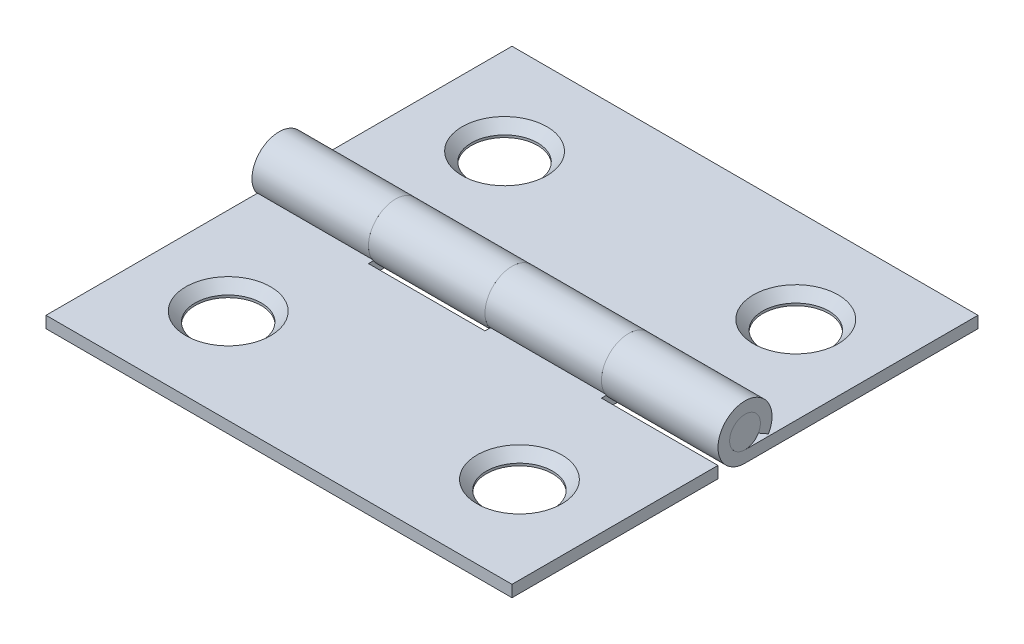
SolidWorks part; units mm, degrees
ref_plane "Front Plane" through (0, 0, 0) normal (0, 0, 1) x (1, 0, 0)
ref_plane "Top Plane" through (0, 0, 0) normal (0, 1, 0) x (1, 0, 0)
ref_plane "Right Plane" through (0, 0, 0) normal (1, 0, 0) x (0, 0, -1)
sketch "Sketch1" plane through (0, 0, 0) normal (0, 1, 0) x (1, 0, 0)
  line L0 (-12.7, 0) -> (12.7, 0) construction
  line L1 (-12.7, -12.7) -> (-12.7, 12.7) construction
  line L2 (-12.7, -12.7) -> (-7.9248, -12.7) construction
  line L4 (-7.9248, -12.7) -> (7.9502, -12.7) construction
  line L5 (12.7254, -12.7) -> (12.7254, -7.5438) construction
  line L6 (7.9502, -12.7) -> (12.7254, -12.7) construction
  line L7 (-12.7, 12.7) -> (-7.9248, 12.7) construction
  line L8 (-7.9248, 12.7) -> (7.9502, 12.7) construction
  line L9 (7.9502, 12.7) -> (23.8252, 12.7) construction
  line L10 (23.8252, 12.7) -> (28.6004, 12.7) construction
  line L11 (7.9502, -9.8552) -> (7.9502, -5.2324) construction
  line L12 (7.9502, -7.5438) -> (12.7254, -7.5438) construction
  point P3 (7.9502, -9.3472)
  point P4 (0, 0)
  point P8 (-12.7, 0)
  point P17 (-6.35, 0)
  point P21 (7.9502, -7.5438)
  dimension "Frame Leaf Height" = 25.4
  dimension "Overall Width" = 25.4
  dimension "Hole to End 1" = 4.7752
  dimension "Hole to End 2" = 4.7752
  dimension "D1" = 4.7752
  dimension "D2" = 4.7752
  dimension "D4" = 15.875
  dimension "D6" = 15.875
  dimension "Knuckle Length" = 6.35
  dimension "Hole Chamfer Dia" = 4.6228
  dimension "Hole Center to Pin" = 7.5438
  dimension "Door Leaf Height" = 25.4254
  dimension "Mounting Hole Diameter" = 3.6068
  dimension "D3" = 15.875
  dimension "Frame Leaf Width" = 12.7
  dimension "Door Leaf Width" = 12.7
sketch "Sketch2" plane through (0, 0, 0) normal (1, 0, 0) x (0, 0, -1)
  line L2 (0, -1.4732) -> (0, -0.8382) construction
  line L4 (0, 0.8382) -> (0, -0.8382) construction
  point P8 (0, 0)
  dimension "Leaf Thickness" = 0.635
  dimension "Pin Diameter" = 1.6764
sketch "Sketch3" plane through (0, 0, 0) normal (1, 0, 0) x (0, 0, -1)
  line L3 (0, 0) -> (-1.4732, -0.8382) construction
  line L4 (0, -1.4732) -> (-12.7, -1.4732)
  line L5 (-12.7, -1.4732) -> (-12.7, -0.8382)
  line L7 (-12.7, -0.8382) -> (0, -0.8382)
  line L8 (-12.7, 0) -> (12.7, 0) construction
  line L9 (-0.7285, -0.4145) -> (-1.2805, -0.7285)
  line L11 (-1.4732, 0) -> (-1.4732, -0.8382) construction
  circle A4 centre (0, 0) radius 0.8382 construction
  circle A5 centre (0, 0) radius 1.4732 construction
  arc A8 (-0.7285, -0.4145) -> (0, -0.8382) centre (0, 0) cw
  arc A9 (-1.2805, -0.7285) -> (0, -1.4732) centre (0, 0) cw
  point P0 (-1.2805, -0.7285)
  point P13 (-0.7285, -0.4145)
extrude "Boss-Extrude1" add sketch "Sketch3" along normal mid plane 25.4
sketch "Sketch4" plane through (0, 0, 0) normal (0, 1, 0) x (1, 0, 0)
  line L0 (-12.7, -1.4732) -> (12.7, -1.4732) construction
  line L1 (-12.7, -1.4732) -> (12.7, -1.4732) construction
  line L2 (12.7, 1.4732) -> (-12.7, 1.4732) construction
  line L3 (12.7, 1.4732) -> (-12.7, 1.4732) construction
  line L4 (-6.35, -1.4732) -> (-6.35, 1.4732)
  line L6 (-6.35, 1.4732) -> (0, 1.4732)
  line L7 (0, -1.4732) -> (-6.35, -1.4732)
  line L8 (0, 1.4732) -> (0, -1.4732)
  point P8 (-6.35, 0)
  dimension "D1" = 6.35
extrude "Cut-Extrude1" cut sketch "Sketch4" against normal through all both and the other way through all
pattern_linear "LPattern1" count 6 spacing 12.7 along (1, 0, 0) of "Cut-Extrude1"
sketch "Sketch5" plane through (0, -0.8382, 0) normal (0, 1, 0) x (1, 0, 0)
  line L0 (7.9502, -7.5438) -> (-7.9248, -7.5438) construction
  line L1 (0, -7.5438) -> (0, -12.7) construction
  line L2 (-7.9248, -7.5438) -> (-7.9248, -12.7) construction
  line L3 (12.7, -12.7) -> (-12.7, -12.7) construction
  circle A0 centre (7.9502, -7.5438) radius 2.3114
  circle A2 centre (-7.9248, -7.5438) radius 2.3114
extrude "Cut-Extrude2" cut sketch "Sketch5" against normal through all draft 45
sketch "Sketch9" plane through (0, 0, 0) normal (0, 1, 0) x (1, 0, 0)
  circle A0 centre (7.9502, -7.5438) radius 1.8034
  circle A2 centre (-7.9248, -7.5438) radius 1.8034
  dimension "D1" = 3.6068
extrude "Cut-Extrude3" cut sketch "Sketch9" against normal through all both and the other way through all
pattern_circular "CirPattern1" count 2 over 360 about axis through (0, 0, 0) along (0, 1, 0) of bodies 110 107
sketch "Sketch6" plane through (0, 0, 0) normal (1, 0, 0) x (0, 0, -1)
  circle A0 centre (0, 0) radius 0.8382
  dimension "D1" = 1.6764
extrude "Boss-Extrude2" add sketch "Sketch6" along normal mid plane 25.4 separate body
sketch "Sketch7" plane through (0, 0, 0) normal (1, 0, 0) x (0, 0, -1)
  line L0 (-0.8382, 0) -> (0.8382, 0) construction
  line L1 (-12.7, 0) -> (12.7, 0) construction
  line L2 (12.7, -0.8382) -> (12.7, -1.4732) construction
  line L3 (12.7, -0.8382) -> (12.7, -1.4732) construction
  line L4 (12.7, -1.4732) -> (-12.7, -1.4732) construction
  line L5 (-12.7, -1.4732) -> (-12.7, -0.8382)
  point P6 (0, 0)
  point P8 (0.8382, 0)
  point P9 (-0.8382, 0)
  point P12 (12.7, -0.8382)
  point P13 (12.7, -1.4732)
  point P14 (-12.7, -1.4732)
  dimension "D1" = 1.6764
  dimension "D2" = 25.4
  dimension "D3" = 0.635
sketch "Sketch8" plane through (0, 0, 0) normal (0, 1, 0) x (1, 0, 0)
  line L0 (-10.2362, -7.5438) -> (-5.6134, -7.5438) construction
  line L2 (5.6388, -7.5438) -> (10.2616, -7.5438) construction
  line L3 (-7.9248, -5.2324) -> (-7.9248, -9.8552) construction
  line L5 (7.9502, -5.2324) -> (7.9502, -9.8552) construction
  line L6 (-7.9502, 9.8552) -> (-7.9502, 5.2324) construction
  line L7 (-10.2616, 7.5438) -> (-5.6388, 7.5438) construction
  line L10 (7.9248, 9.8552) -> (7.9248, 5.2324) construction
  line L11 (5.6134, 7.5438) -> (10.2362, 7.5438) construction
  line L12 (7.9248, 7.5438) -> (9.5592, 9.1782) construction
  circle A1 centre (-7.9248, -7.5438) radius 2.3114 construction
  circle A3 centre (7.9502, -7.5438) radius 2.3114 construction
  circle A4 centre (-7.9502, 7.5438) radius 2.3114 construction
  circle A6 centre (7.9248, 7.5438) radius 2.3114 construction
  circle A7 centre (7.9248, 7.5438) radius 2.3114 construction
  point P2 (-12.7, 0)
  point P7 (-7.9248, -7.5438)
  point P19 (7.9502, -7.5438)
  point P25 (-12.7, 12.7)
  point P26 (28.6004, 12.7)
  point P28 (-12.7, -12.7)
  point P30 (12.7254, -12.7)
  point P32 (-10.2362, -7.5438)
  point P33 (-7.9248, -5.2324)
  point P34 (-5.6134, -7.5438)
  point P35 (-7.9248, -9.8552)
  point P40 (10.2616, -7.5438)
  point P41 (7.9502, -9.8552)
  point P42 (5.6388, -7.5438)
  point P43 (7.9502, -5.2324)
  point P67 (7.9502, -12.7)
  point P69 (-7.9248, -12.7)
  point P71 (-7.9248, 12.7)
  point P73 (-7.9502, 7.5438)
  point P76 (7.9248, 7.5438)
  point P77 (23.8252, 12.7)
  point P78 (7.9502, 12.7)
  point P82 (-7.9502, 9.8552)
  point P83 (-10.2616, 7.5438)
  point P84 (-7.9502, 5.2324)
  point P85 (-5.6388, 7.5438)
  point P90 (7.9248, 5.2324)
  point P91 (5.6134, 7.5438)
  point P92 (7.9248, 9.8552)
  point P93 (10.2362, 7.5438)
  point P97 (9.5592, 9.1782)
  dimension "D1" = 45
equation "\"D1@Sketch1\"=\"Hole to End 1@Sketch1\""
equation "\"D2@Sketch1\"=\"Hole to End 2@Sketch1\""
equation "\"D6@Sketch1\"=\"D4@Sketch1\""
equation "\"D1@Boss-Extrude1\" = \"Frame Leaf Height@Sketch1\""
equation "\"D1@Sketch4\"=\"Knuckle Length@Sketch1\""
equation "\"D3@LPattern1\"=\"Knuckle Length@Sketch1\"*2"
equation "\"D1@Sketch6\"=\"Pin Diameter@Sketch2\""
equation "\"D1@Boss-Extrude2\" = \"Frame Leaf Height@Sketch1\""
equation "\"D1@Sketch7\"=\"Pin Diameter@Sketch2\""
equation "\"D2@Sketch7\"=\"Overall Width@Sketch1\""
equation "\"D3@Sketch7\"=\"Leaf Thickness@Sketch2\""
equation "\"Knuckle Length@Sketch1\"=\"Frame Leaf Height@Sketch1\" / 4"
equation "\"Hole to End 2@Sketch1\"=\"Hole to End 1@Sketch1\""
equation "\"D1@Sketch9\"=\"Mounting Hole Diameter@Sketch1\""
equation "\"Hole Chamfer Dia@Sketch1\"=\"Mounting Hole Diameter@Sketch1\"+.04"
